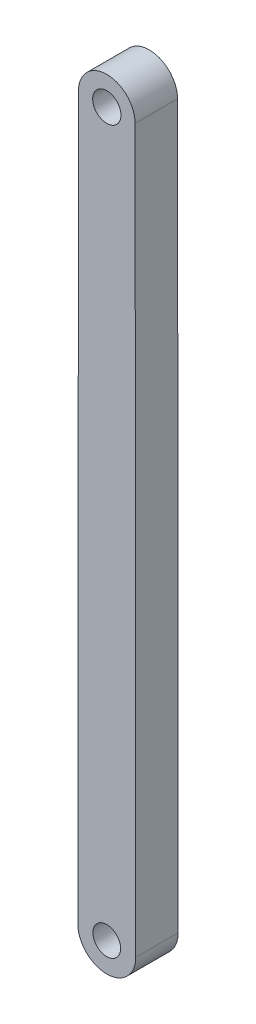
SolidWorks part; units mm, degrees
ref_plane "前视基准面" through (0, 0, 0) normal (0, 0, 1) x (1, 0, 0)
ref_plane "上视基准面" through (0, 0, 0) normal (0, 1, 0) x (1, 0, 0)
ref_plane "右视基准面" through (0, 0, 0) normal (1, 0, 0) x (0, 0, -1)
sketch "草图1" plane through (0, 0, 0) normal (0, 0, 1) x (1, 0, 0)
  line L0 (-427.9235, 34.4681) -> (-427.9687, 85.4681)
  line L1 (-431.9687, 85.4683) -> (-432.018, 34.4683)
  circle A0 centre (-429.9687, 85.4663) radius 1
  arc A1 (-432.018, 34.4683) -> (-427.9235, 34.4681) centre (-429.9708, 34.4663) ccw
  arc A2 (-427.9687, 85.4681) -> (-431.9687, 85.4683) centre (-429.9687, 85.4663) ccw
  circle A3 centre (-429.9708, 34.4663) radius 0.9804
  dimension "D2" = 2
  dimension "D3" = 2
  dimension "D1" = 51
extrude "凸台-拉伸1" add sketch "草图1" along normal blind 3
